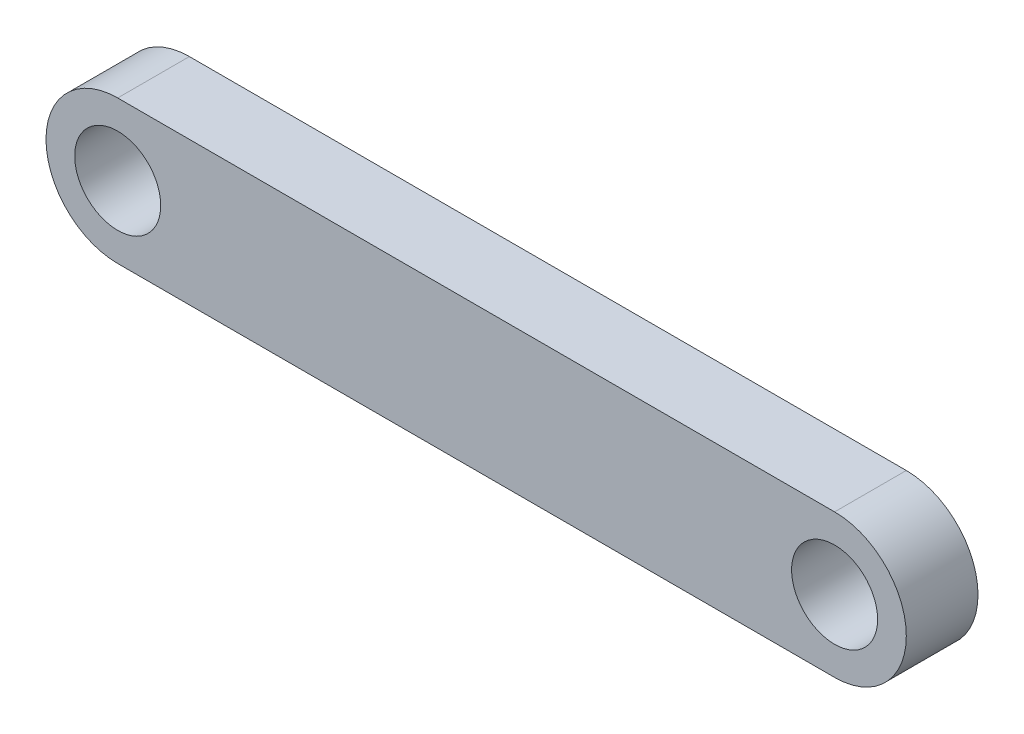
SolidWorks part; units mm, degrees
ref_plane "Front Plane" through (0, 0, 0) normal (0, 0, 1) x (1, 0, 0)
ref_plane "Top Plane" through (0, 0, 0) normal (0, 1, 0) x (1, 0, 0)
ref_plane "Right Plane" through (0, 0, 0) normal (1, 0, 0) x (0, 0, -1)
sketch "Sketch1" plane through (0, 0, 0) normal (0, 0, 1) x (1, 0, 0)
  line L0 (25, 0) -> (-25, 0) construction
  line L1 (25, -5) -> (-25, -5)
  line L2 (25, 5) -> (-25, 5)
  arc A0 (25, -5) -> (25, 5) centre (25, 0) ccw
  arc A1 (-25, 5) -> (-25, -5) centre (-25, 0) ccw
  circle A2 centre (-25, 0) radius 3
  circle A3 centre (25, 0) radius 3
  point P2 (0, 0)
  dimension "D2" = 5
  dimension "D3" = 6
  dimension "D4" = 6
  dimension "D1" = 50
extrude "Boss-Extrude1" add sketch "Sketch1" along normal blind 5
sketch "Sketch2" plane through (0, 0, 5) normal (0, 0, 1) x (1, 0, 0)
  circle A0 centre (-25, 0) radius 3
